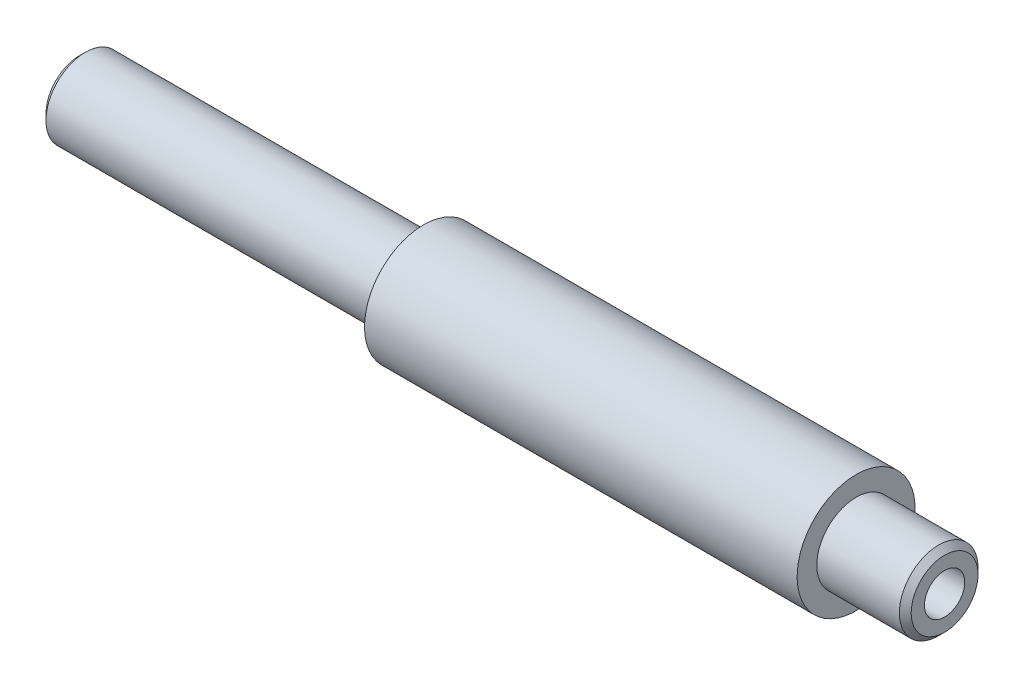
SolidWorks part; units mm, degrees
material "Acier allié inoxydable"
ref_plane "Face" through (0, 0, 0) normal (0, 0, 1) x (1, 0, 0)
ref_plane "Dessus" through (0, 0, 0) normal (0, 1, 0) x (1, 0, 0)
ref_plane "Droite" through (0, 0, 0) normal (1, 0, 0) x (0, 0, -1)
sketch "Esquisse1" plane through (0, 0, 0) normal (0, 0, 1) x (1, 0, 0)
  line L0 (0, 0) -> (0, 2)
  line L1 (0, 2) -> (17.5, 2)
  line L2 (17.5, 2) -> (17.5, 3)
  line L3 (17.5, 3) -> (39.5, 3)
  line L4 (39.5, 3) -> (39.5, 2)
  line L5 (39.5, 2) -> (44, 2)
  line L6 (44, 2) -> (44, 0)
  line L7 (44, 0) -> (0, 0) construction
  line L8 (0, 0) -> (44, 0)
  dimension "D1" = 4
  dimension "D2" = 17.5
  dimension "D3" = 6
  dimension "D4" = 22
  dimension "D5" = 4.5
  dimension "D6" = 4
revolve "Révolution1" add sketch "Esquisse1" angle 360 about L7
hole_wizard "Trou taraudé M2.51" positions "Esquisse6" profile "Esquisse5" tap size "M2.5" standard "Iso"
sketch "Esquisse6" plane through (0, 0, 0) normal (-1, 0, 0) x (0, 0, 1)
  point P0 (0, 0)
sketch "Esquisse5" plane through (0, 0, 0) normal (0, 1, 0) x (0, 0, 1)
  line L0 (0, 0) -> (0, 8.6159)
  line L1 (0, 8.6159) -> (1.025, 8)
  line L2 (1.025, 8) -> (1.025, 0)
  line L5 (1.025, 0) -> (0, 0)
  line L10 (0, 8.6159) -> (-1.025, 8) construction
  line L11 (0, -6.35) -> (0, 107.95) construction
  dimension "Diamètre du trou pour taraudage" = 2.05
  dimension "Profondeur du trou pour taraudage" = 8
  dimension "Angle de pointe" = 118
cosmetic thread "Filetage de perçage4" parameters "D1"=6, "D2"=2.5
hole_wizard "Trou taraudé M2.52" positions "Esquisse8" profile "Esquisse7" tap size "M2.5" standard "Iso"
sketch "Esquisse8" plane through (44, 0, 0) normal (1, 0, 0) x (0, 0, -1)
  point P0 (0, 0)
cosmetic thread "Filetage de perçage5" parameters "D1"=6, "D2"=2.5
sketch "Esquisse7" plane through (44, 0, 0) normal (0, 1, 0) x (0, 0, -1)
  line L0 (0, 0) -> (0, 8.6159)
  line L1 (0, 8.6159) -> (1.025, 8)
  line L2 (1.025, 8) -> (1.025, 0)
  line L5 (1.025, 0) -> (0, 0)
  line L10 (0, 8.6159) -> (-1.025, 8) construction
  line L11 (0, -6.35) -> (0, 107.95) construction
  dimension "Diamètre du trou pour taraudage" = 2.05
  dimension "Profondeur du trou pour taraudage" = 8
  dimension "Angle de pointe" = 118
chamfer "Chanfrein1" distance 0.3 angle 45 2 edges at (44, 2, 0) (0, 2, 0)
